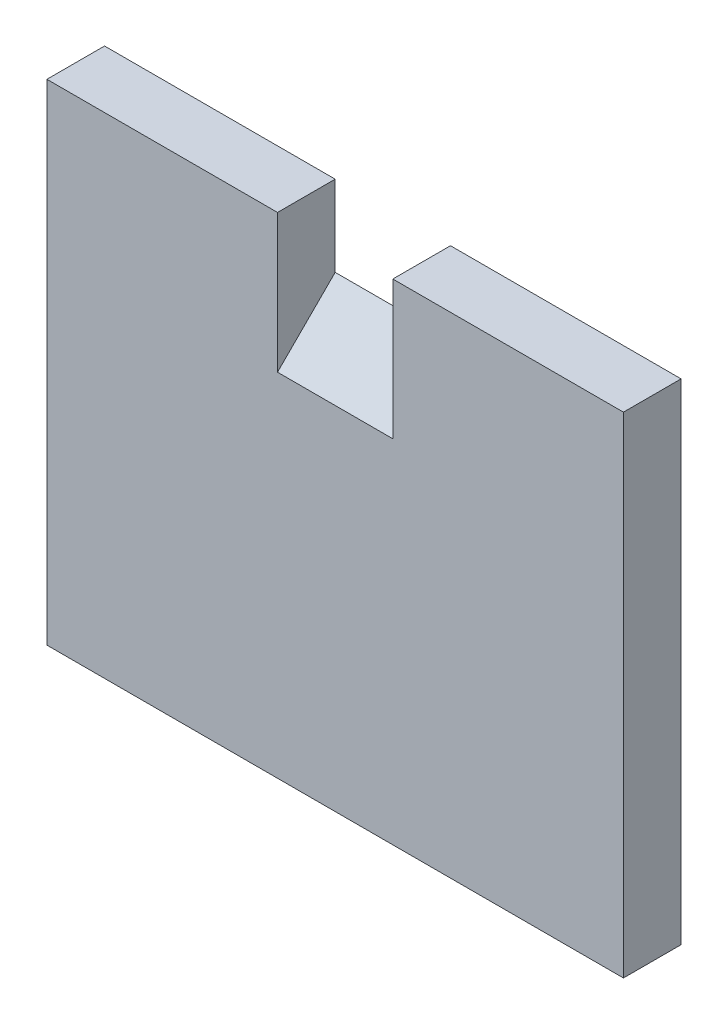
SolidWorks part; units mm, degrees
ref_plane "Plan de face" through (0, 0, 0) normal (0, 0, 1) x (1, 0, 0)
ref_plane "Plan de dessus" through (0, 0, 0) normal (0, 1, 0) x (1, 0, 0)
ref_plane "Plan de droite" through (0, 0, 0) normal (1, 0, 0) x (0, 0, -1)
sketch "Esquisse1" plane through (0, 0, 0) normal (0, 0, 1) x (1, 0, 0)
  line L1 (-50, -42.5) -> (50, -42.5)
  line L2 (-50, -42.5) -> (-50, 42.5)
  line L3 (-50, 42.5) -> (-10, 42.5)
  line L4 (50, -42.5) -> (50, 42.5)
  line L5 (-50, -42.5) -> (50, 42.5) construction
  line L6 (-50, 42.5) -> (50, -42.5) construction
  line L7 (0, 28.5) -> (10, 28.5)
  line L8 (0, 28.5) -> (-10, 28.5)
  line L9 (50, 42.5) -> (10, 42.5)
  line L10 (10, 42.5) -> (10, 28.5)
  line L11 (-10, 42.5) -> (-10, 28.5)
  point P0 (0, 0)
  dimension "D1" = 100
  dimension "D2" = 85
  dimension "D4" = 10
  dimension "D5" = 10
extrude "Boss.-Extru.1" add sketch "Esquisse1" along normal blind 10 contours L3 L11 L8 L7 L10 L9 L4 L1 L2
ref_plane "Plan1" through (50, 0, 0) normal (1, 0, 0) x (0, 0, -1)
sketch "Esquisse2" plane through (50, 0, 0) normal (1, 0, 0) x (0, 0, -1)
  line L0 (-10, 42.5) -> (-10, 28.5) construction
  line L1 (-10, -42.5) -> (-10, 42.5) construction
  line L2 (-10, 28.5) -> (0, 18.5)
  line L3 (0, -42.5) -> (0, 42.5) construction
  line L4 (-10, 28.5) -> (0, 28.5)
  line L5 (0, 28.5) -> (0, 18.5)
  dimension "D1" = 14
  dimension "D2" = 45
extrude "Enlèv. mat.-Extru.1" cut sketch "Esquisse2" against normal blind 60 contours L4 L5 L2
ref_plane "Plan2" through (50, 28.5, 10) normal (0, 0, -1) x (-1, 0, 0)
sketch "Esquisse4" plane through (50, 0, 0) normal (1, 0, 0) x (0, 0, -1)
  line L0 (-10, 28.5) -> (0, 18.5)
  line L1 (-10, 28.5) -> (0, 18.5) construction
  line L2 (-10, 28.5) -> (0, 28.5) construction
  line L3 (0, 18.5) -> (0, 28.5)
  line L4 (0, 28.5) -> (-10, 28.5)
extrude "Boss.-Extru.2" add sketch "Esquisse4" against normal blind 40
sketch "Esquisse5" plane through (50, 0, 0) normal (1, 0, 0) x (0, 0, -1)
  line L0 (-10, 42.5) -> (-10, 12.5)
  line L1 (-10, -42.5) -> (-10, 42.5) construction
  line L2 (-10, 12.5) -> (0, 12.5)
  line L3 (0, -42.5) -> (0, 42.5) construction
  line L4 (0, 12.5) -> (0, 42.5)
  line L5 (0, 42.5) -> (-10, 42.5)
extrude "Boss.-Extru.3" add sketch "Esquisse5" against normal blind 60 contours L0 L2 L4 L5
sketch "Esquisse6" plane through (50, 0, 0) normal (1, 0, 0) x (0, 0, -1)
  line L0 (-10, 42.5) -> (0, 42.5)
  line L1 (0, 42.5) -> (0, 28.5)
  line L2 (0, -42.5) -> (0, 42.5) construction
  line L3 (0, 28.5) -> (-10, 28.5)
  line L4 (-10, -42.5) -> (-10, 42.5) construction
  line L5 (-10, 28.5) -> (-10, 42.5)
  dimension "D1" = 14
extrude "Enlèv. mat.-Extru.2" cut sketch "Esquisse6" against normal blind 60
sketch "Esquisse7" plane through (50, 28.5, 10) normal (0, 0, -1) x (-1, 0, 0)
  line L0 (0, 0) -> (0, 14)
  line L1 (0, 0) -> (0, -13.2469)
  line L2 (0, -71) -> (0, 0) construction
sketch "Esquisse8" plane through (50, 0, 0) normal (1, 0, 0) x (0, 0, -1)
sketch "Esquisse9" plane through (50, 0, 0) normal (1, 0, 0) x (0, 0, -1)
  line L0 (-10, 28.5) -> (0, 28.5)
  line L1 (0, 28.5) -> (0, 42.5)
  line L2 (0, 42.5) -> (-10, 42.5)
  line L3 (-10, 42.5) -> (-10, 28.5)
  dimension "D1" = 14
extrude "Boss.-Extru.4" add sketch "Esquisse9" against normal blind 40
sketch "Esquisse11" plane through (50, 0, 0) normal (1, 0, 0) x (0, 0, -1)
  line L0 (-10, 42.5) -> (-10, 28.5)
  line L1 (-10, -42.5) -> (-10, 42.5) construction
  line L2 (-10, 28.5) -> (0, 18.5)
  line L3 (0, -42.5) -> (0, 42.5) construction
  line L4 (0, 18.5) -> (0, 28.5)
  line L5 (0, 28.5) -> (-10, 28.5)
  dimension "D1" = 14
  dimension "D2" = 45
extrude "Enlèv. mat.-Extru.3" cut sketch "Esquisse11" against normal blind 60 contours L4 L5 L2
sketch "Esquisse12" plane through (50, 0, 0) normal (1, 0, 0) x (0, 0, -1)
  line L0 (-10, 28.5) -> (0, 28.5)
  line L1 (0, 28.5) -> (0, 18.5)
  line L2 (0, 18.5) -> (-10, 28.5)
extrude "Boss.-Extru.5" add sketch "Esquisse12" against normal blind 40
sketch "Esquisse13" plane through (50, 0, 0) normal (1, 0, 0) x (0, 0, -1)
  line L0 (-10, 42.5) -> (-10, 28.5)
  line L1 (-10, -42.5) -> (-10, 42.5) construction
  line L2 (-10, 28.5) -> (0, 28.5)
  line L3 (0, 28.5) -> (0, -2.8986)
  line L4 (0, -42.5) -> (0, 42.5) construction
  line L5 (0, -2.8986) -> (-10, -2.8986)
  line L6 (-10, -2.8986) -> (-10, 28.5)
  dimension "D1" = 14
extrude "Boss.-Extru.6" add sketch "Esquisse13" against normal blind 60 contours L6 L5 L3 L2
sketch "Esquisse16" plane through (50, 0, 0) normal (1, 0, 0) x (0, 0, -1)
  line L0 (-10, 42.5) -> (-10, 28.5) construction
  line L1 (-10, 28.5) -> (0, 28.5) construction
  line L2 (0, 28.5) -> (-10, 18.5) construction
  line L3 (-10, 28.5) -> (-10, 15.2531) construction
  line L4 (-10, 18.5) -> (-10, 28.5) construction
  line L5 (-10, 28.5) -> (0, 28.5)
  line L6 (0, 28.5) -> (-10, 18.5)
  line L7 (-10, 18.5) -> (-10, 28.5)
  dimension "D1" = 45
extrude "Enlèv. mat.-Extru.9" cut sketch "Esquisse16" against normal blind 60 contours L5 L6 L7
sketch "Esquisse17" plane through (50, 0, 0) normal (1, 0, 0) x (0, 0, -1)
  line L0 (-10, 28.5) -> (0, 28.5)
  line L1 (0, 28.5) -> (-10, 18.5)
  line L2 (-10, 18.5) -> (-10, 28.5)
extrude "Boss.-Extru.7" add sketch "Esquisse17" against normal blind 40
